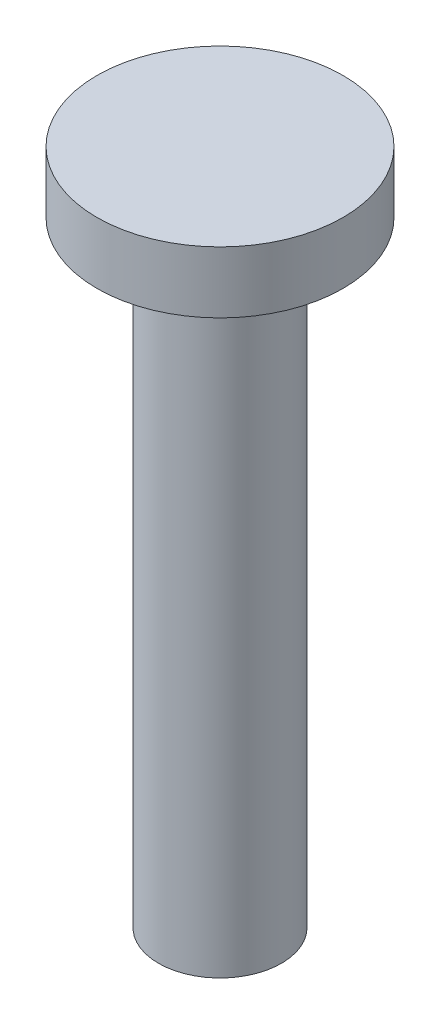
SolidWorks part; units mm, degrees
ref_plane "Front Plane" through (0, 0, 0) normal (0, 0, 1) x (1, 0, 0)
ref_plane "Top Plane" through (0, 0, 0) normal (0, 1, 0) x (1, 0, 0)
ref_plane "Right Plane" through (0, 0, 0) normal (1, 0, 0) x (0, 0, -1)
sketch "Sketch1" plane through (0, 0, 0) normal (0, 1, 0) x (1, 0, 0)
  circle A0 centre (0, 0) radius 3.175
extrude "Boss-Extrude1" add sketch "Sketch1" along normal blind 31.75
sketch "Sketch2" plane through (0, 31.75, 0) normal (0, 1, 0) x (1, 0, 0)
  circle A0 centre (0, 0) radius 6.35
extrude "Boss-Extrude2" add sketch "Sketch2" along normal blind 3.175
